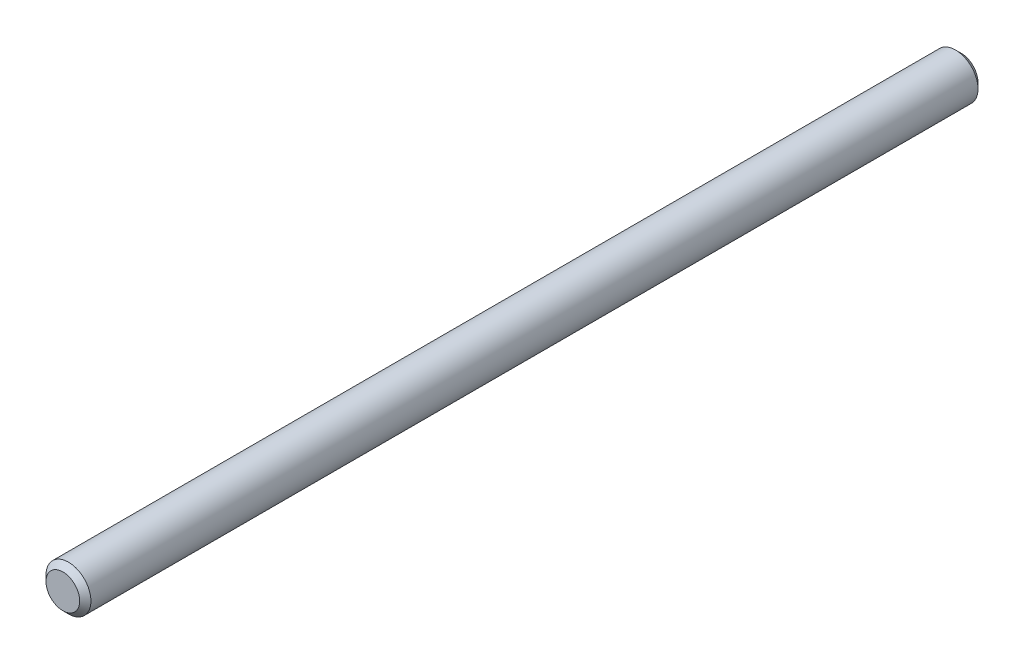
SolidWorks part; units mm, degrees
ref_plane "前视基准面" through (0, 0, 0) normal (0, 0, 1) x (1, 0, 0)
ref_plane "上视基准面" through (0, 0, 0) normal (0, 1, 0) x (1, 0, 0)
ref_plane "右视基准面" through (0, 0, 0) normal (1, 0, 0) x (0, 0, -1)
sketch "草图1" plane through (0, 0, 0) normal (0, 0, 1) x (1, 0, 0)
  circle A0 centre (0, 0) radius 2
extrude "凸台-拉伸1" add sketch "草图1" against normal blind 80
chamfer "倒角1" distance 0.5 angle 45 2 edges at (2, 0, -80) (2, 0, 0)
